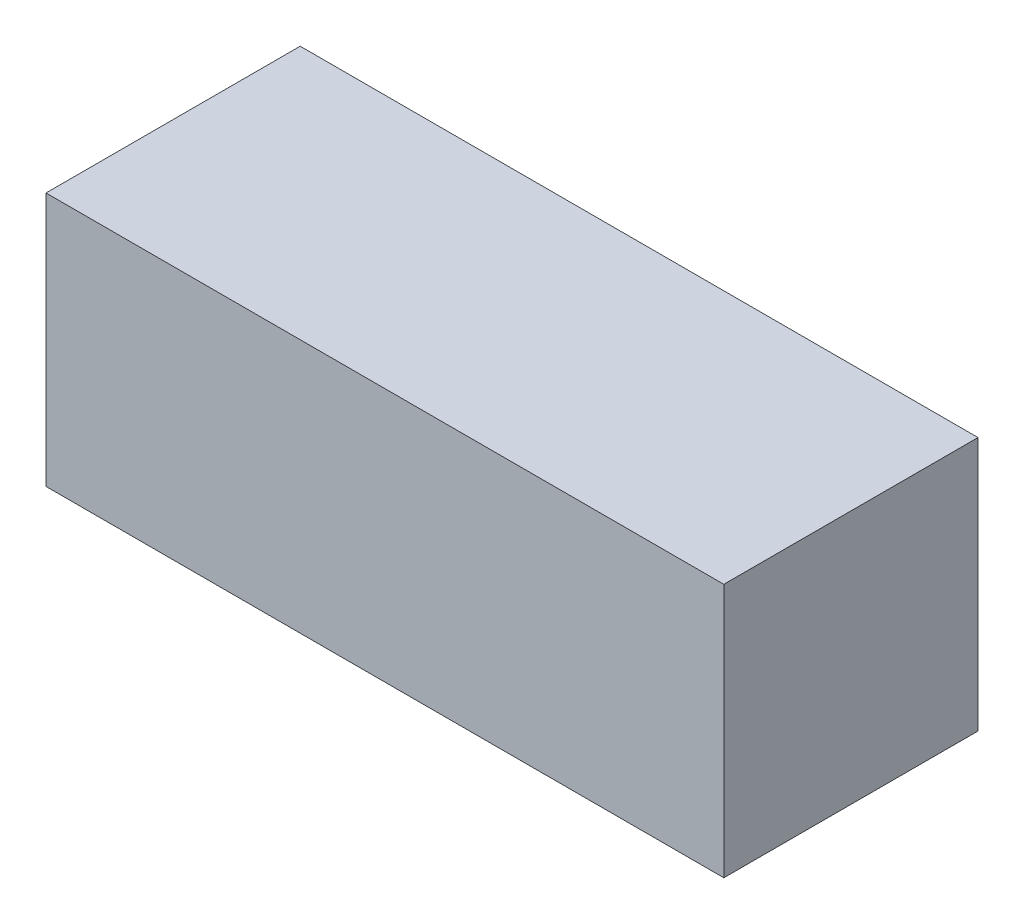
SolidWorks part; units mm, degrees
material "Pine"
ref_plane "Front Plane" through (0, 0, 0) normal (0, 0, 1) x (1, 0, 0)
ref_plane "Top Plane" through (0, 0, 0) normal (0, 1, 0) x (1, 0, 0)
ref_plane "Right Plane" through (0, 0, 0) normal (1, 0, 0) x (0, 0, -1)
sketch "Sketch1" plane through (0, 0, 0) normal (0, 0, 1) x (1, 0, 0)
  line L1 (-50.8, 19.05) -> (50.8, 19.05)
  line L2 (-50.8, 19.05) -> (-50.8, -19.05)
  line L3 (-50.8, -19.05) -> (50.8, -19.05)
  line L4 (50.8, 19.05) -> (50.8, -19.05)
  point P4 (0, 19.05)
  point P6 (50.8, 0)
  dimension "D1" = 101.6
  dimension "D2" = 38.1
extrude "Boss-Extrude1" add sketch "Sketch1" along normal blind 38.1
